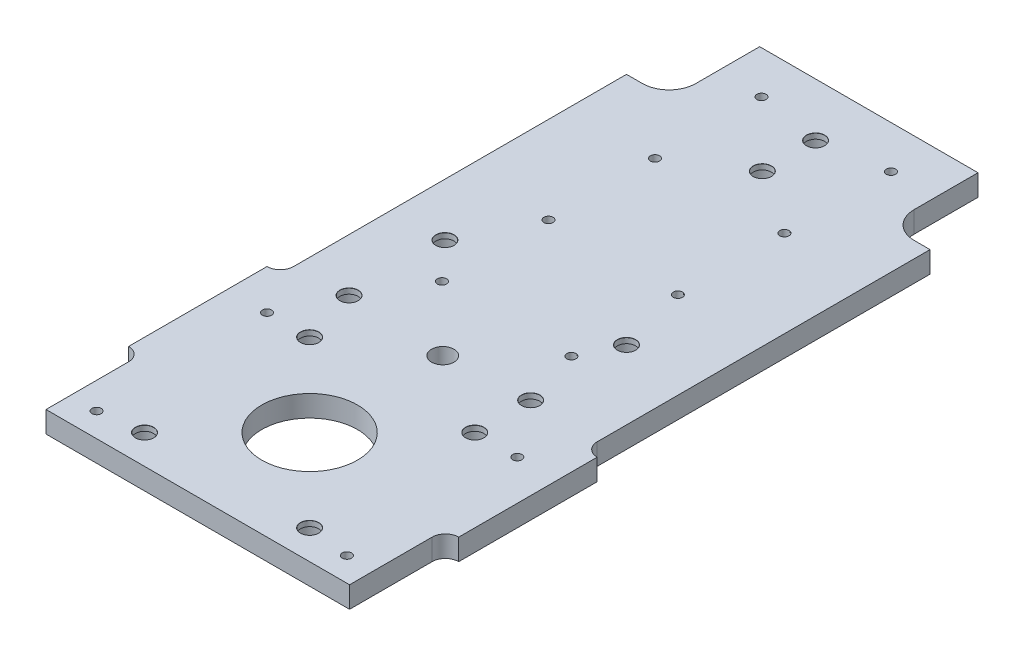
SolidWorks part; units mm, degrees
ref_plane "Top" through (0, 0, 0) normal (0, 0, 1) x (1, 0, 0)
ref_plane "Front" through (0, 0, 0) normal (0, 1, 0) x (1, 0, 0)
ref_plane "Right" through (0, 0, 0) normal (1, 0, 0) x (0, 0, -1)
sketch "Plate Main Sketch" plane through (-158.0855, 0, 24.6791) normal (0, 1, 0) x (-1, 0, 0)
  line L1 (-178.5855, -24.6791) -> (-137.5855, -24.6791)
  line L2 (-127.0855, 57.3209) -> (-127.0855, 83.3209)
  line L3 (-129.5855, 101.3209) -> (-186.5855, 101.3209)
  line L4 (-129.5855, 101.3209) -> (-129.5855, 85.8209)
  line L5 (-158.0855, 101.3209) -> (-158.0855, -24.6791) construction
  line L6 (-178.5855, -12.6791) -> (-178.5855, -24.6791)
  line L7 (-129.5855, 54.8209) -> (-129.5855, -7.6791)
  line L8 (-129.5855, -7.6791) -> (-132.5855, -7.6791)
  line L9 (-137.5855, -12.6791) -> (-137.5855, -24.6791)
  line L10 (-186.5855, -7.6791) -> (-183.5855, -7.6791)
  line L11 (-186.5855, 54.8209) -> (-186.5855, -7.6791)
  line L12 (-189.0855, 57.3209) -> (-189.0855, 83.3209)
  line L13 (-186.5855, 101.3209) -> (-186.5855, 85.8209)
  line L14 (-181.5855, 96.8209) -> (-134.5855, 96.8209) construction
  line L15 (-134.5855, 96.8209) -> (-134.5855, 64.8209) construction
  line L16 (-134.5855, 64.8209) -> (-181.5855, 64.8209) construction
  line L17 (-181.5855, 64.8209) -> (-181.5855, 96.8209) construction
  line L18 (-145.9294, -16.6791) -> (-145.9294, 43.3209) construction
  arc A0 (-129.5855, 85.8209) -> (-127.0855, 83.3209) centre (-127.0855, 85.8209) ccw
  arc A1 (-129.5855, 54.8209) -> (-127.0855, 57.3209) centre (-127.0855, 54.8209) cw
  arc A2 (-132.5855, -7.6791) -> (-137.5855, -12.6791) centre (-132.5855, -12.6791) ccw
  arc A3 (-183.5855, -7.6791) -> (-178.5855, -12.6791) centre (-183.5855, -12.6791) cw
  arc A4 (-186.5855, 54.8209) -> (-189.0855, 57.3209) centre (-189.0855, 54.8209) ccw
  arc A5 (-186.5855, 85.8209) -> (-189.0855, 83.3209) centre (-189.0855, 85.8209) cw
  circle A6 centre (-134.5855, 96.8209) radius 0.8649
  circle A7 centre (-134.5855, 64.8209) radius 0.8649
  circle A8 centre (-181.5855, 64.8209) radius 0.8649
  circle A9 centre (-181.5855, 96.8209) radius 0.8649
  circle A10 centre (-170.2416, -16.6791) radius 0.8649
  circle A11 centre (-170.2416, 3.3209) radius 0.8649
  circle A12 centre (-170.2416, 23.3209) radius 0.8649
  circle A13 centre (-170.2416, 43.3209) radius 0.8649
  circle A14 centre (-145.9294, -16.6791) radius 0.8649
  circle A15 centre (-145.9294, 3.3209) radius 0.8649
  circle A16 centre (-145.9294, 23.3209) radius 0.8649
  circle A17 centre (-145.9294, 43.3209) radius 0.8649
  circle A18 centre (-158.0855, 80.3209) radius 8.9827
  circle A19 centre (-158.0855, 55.3209) radius 2.1117
  point P27 (-174.0091, -32.6791)
  point P28 (0, 0)
  point P44 (0, 0)
  point P57 (0, 0)
  point P58 (-171.5958, -72.6791)
  point P59 (0, 0)
  point P60 (-186.5855, -150.6791)
  point P61 (-137.5855, -36.6791)
  point P62 (0, 0)
  point P63 (0, 0)
  point P64 (-186.5855, -43.7528)
  point P65 (0, 0)
  point P66 (-186.5855, -150.6791)
  point P67 (-98.9604, -140.0455)
  point P68 (-49.0033, -92.749)
  point P70 (-29.5689, -10.1776)
  point P71 (-66.8513, 65.6336)
  point P72 (-121.2003, 98.2646)
  dimension "D3" = 62
  dimension "D1" = 2.5
  dimension "D2" = 5
  dimension "D8" = 5
  dimension "D11" = 58
  dimension "D15" = 21
  dimension "D16" = 46
  dimension "D4" = 126
  dimension "D5" = 18
  dimension "D6" = 44
  dimension "D7" = 109
  dimension "D9" = 4.5
  dimension "D10" = 36.5
  dimension "D12" = 78
  dimension "D13" = 98
  dimension "D14" = 118
  dimension "D17" = 8
extrude "Extrude Plate Main" add sketch "Plate Main Sketch" along normal blind 4
sketch "Sketch2" plane through (158.0855, 0, 24.6791) normal (0, -1, 0) x (1, 0, 0)
  line L1 (-178.5855, -24.6791) -> (-137.5855, -24.6791) construction
  line L2 (-127.0855, 57.3209) -> (-127.0855, 83.3209) construction
  line L3 (-129.5855, 101.3209) -> (-186.5855, 101.3209) construction
  line L4 (-129.5855, 101.3209) -> (-129.5855, 85.8209) construction
  line L5 (-158.0855, 101.3209) -> (-158.0855, -24.6791) construction
  line L6 (-178.5855, -12.4678) -> (-178.5855, -24.6791) construction
  line L7 (-129.5855, 54.8209) -> (-129.5855, -7.6791) construction
  line L8 (-129.5855, -7.6791) -> (-132.7968, -7.6791) construction
  line L9 (-137.5855, -12.4678) -> (-137.5855, -24.6791) construction
  line L10 (-186.5855, -7.6791) -> (-183.3743, -7.6791) construction
  line L11 (-186.5855, 54.8209) -> (-186.5855, -7.6791) construction
  line L12 (-189.0855, 57.3209) -> (-189.0855, 83.3209) construction
  line L13 (-186.5855, 101.3209) -> (-186.5855, 85.8209) construction
  line L14 (-173.5855, 95.8209) -> (-142.5855, 95.8209) construction
  line L15 (-142.5855, 95.8209) -> (-142.5855, 64.8209) construction
  line L16 (-142.5855, 64.8209) -> (-173.5855, 64.8209) construction
  line L17 (-173.5855, 64.8209) -> (-173.5855, 95.8209) construction
  arc A0 (-129.5855, 85.8209) -> (-127.0855, 83.3209) centre (-127.0855, 85.8209) ccw construction
  arc A1 (-129.5855, 54.8209) -> (-127.0855, 57.3209) centre (-127.0855, 54.8209) cw construction
  arc A2 (-132.7968, -7.6791) -> (-137.5855, -12.4678) centre (-132.7968, -12.4678) ccw construction
  arc A3 (-183.3743, -7.6791) -> (-178.5855, -12.4678) centre (-183.3743, -12.4678) cw construction
  arc A4 (-186.5855, 54.8209) -> (-189.0855, 57.3209) centre (-189.0855, 54.8209) ccw construction
  arc A5 (-186.5855, 85.8209) -> (-189.0855, 83.3209) centre (-189.0855, 85.8209) cw construction
  circle A6 centre (-142.5855, 95.8209) radius 0.8649
  circle A7 centre (-142.5855, 64.8209) radius 0.8649
  circle A8 centre (-173.5855, 64.8209) radius 0.8649
  circle A9 centre (-173.5855, 95.8209) radius 0.8649
  circle A20 centre (-158.0855, -4.6791) radius 0.9359
  circle A21 centre (-158.0855, -14.6791) radius 1.008
  circle A22 centre (-176.6802, 54.3209) radius 1.5374
  circle A23 centre (-176.6802, 36.3209) radius 1.5374
  circle A24 centre (-142.5855, 54.3209) radius 1.5374
  circle A25 centre (-142.5855, 36.3209) radius 1.5374
  point P46 (0, 0)
  point P47 (0, 0)
  point P48 (0, 0)
  point P49 (0, 0)
  dimension "D3" = 62
  dimension "D1" = 2.5
  dimension "D2" = 15.5
  dimension "D8" = 106
  dimension "D11" = 116
  dimension "D12" = 47
  dimension "D4" = 126
  dimension "D5" = 18
  dimension "D6" = 44
  dimension "D7" = 109
  dimension "D9" = 5.5
  dimension "D10" = 36.5
  dimension "D13" = 65
  dimension "D17" = 8
hole_wizard "CBORE for M3 SHCS1" positions "Sketch4" profile "Sketch5" counterbore size "M3" standard "ANSI Metric" end condition through all
sketch "Sketch4" plane through (0, 0, 0) normal (0, -1, 0) x (-1, 0, 0)
  point P0 (15.5, -120.5)
  point P3 (-15.5, -120.5)
  point P6 (-15.5, -89.5)
  point P9 (15.5, -89.5)
  point P12 (18.5947, -79)
  point P15 (-15.5, -79)
  point P18 (-15.5, -61)
  point P21 (18.5947, -61)
  point P24 (0, -20)
  point P27 (0, -10)
  point P31 (0, 0)
sketch "Sketch5" plane through (-15.5, 0, 120.5) normal (1, 0, 0) x (0, 0, -1)
  line L0 (0, 0) -> (0, 4)
  line L1 (1.7, 3.975) -> (1.725, 4)
  line L2 (1.7, 3.975) -> (1.7, 3)
  line L3 (1.7, 3) -> (3, 3)
  line L4 (3, 3) -> (3, 0)
  line L5 (3, 0) -> (0, 0)
  line L11 (0, -6.35) -> (0, 107.95) construction
  line L12 (1.725, 4) -> (0, 4)
  line L13 (-1.7, 3.975) -> (-1.725, 4) construction
  dimension "Thru Hole Dia." = 3.4
  dimension "Thru Hole Depth" = 4
  dimension "C'Bore Dia." = 6
  dimension "C'Bore Depth" = 3
  dimension "Far C'Sink Dia." = 3.45
  dimension "Far C'Sink Angle" = 90
equation "\"M2 Close Fit Hole\"= 2.2"
equation "\"M2.5 Close Fit Hole\"= 2.7"
equation "\"M3 Close Fit Hole\"= 3.2"
equation "\"M4 Close Fit Hole\"= 4.3"
equation "\"M5 Close Fit Hole\"= 5.3"
equation "\"M6 Close Fit Hole\"= 6.3"
equation "\"M7 Close Fit Hole\"= 7.4"
equation "\"M8 Close Fit Hole\"= 8.4"
equation "\"M2 Tap Hole 75%\"= 1.6"
equation "\"M3 Tap Hole 75%\"= 2.5"
equation "\"M4 Tap Hole 75%\"= 3.3"
equation "\"M5 Tap Hole 75%\"= 4.2"
equation "\"M6 Tap Hole 75%\"= 5"
equation "\"M7 Tap Hole 75%\"= 6"
equation "\"M8 Tap Hole 75%\"= 6.8"
